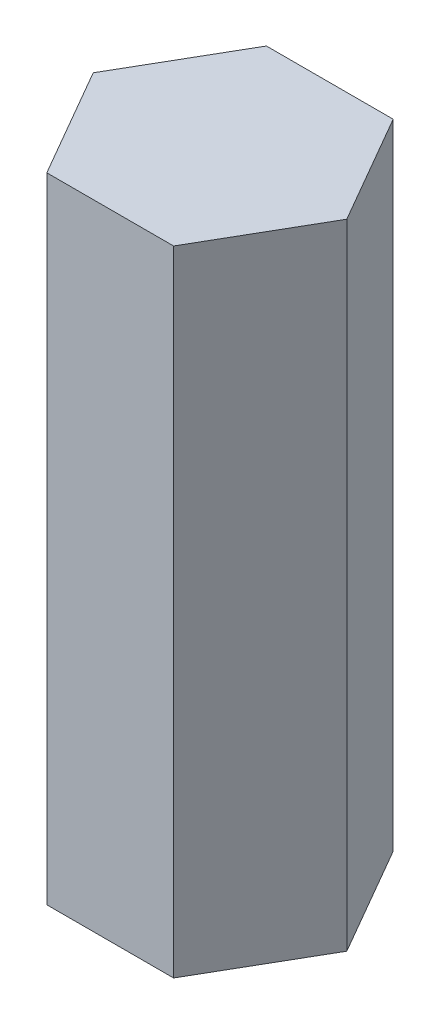
SolidWorks part; units mm, degrees
ref_plane "前视基准面" through (0, 0, 0) normal (0, 0, 1) x (1, 0, 0)
ref_plane "上视基准面" through (0, 0, 0) normal (0, 1, 0) x (1, 0, 0)
ref_plane "右视基准面" through (0, 0, 0) normal (1, 0, 0) x (0, 0, -1)
sketch "草图1" plane through (0, 0, 0) normal (0, 1, 0) x (1, 0, 0)
  line L1 (15, 0) -> (7.5, 12.9904)
  line L2 (7.5, 12.9904) -> (-7.5, 12.9904)
  line L3 (-7.5, 12.9904) -> (-15, 0)
  line L4 (-15, 0) -> (-7.5, -12.9904)
  line L5 (-7.5, -12.9904) -> (7.5, -12.9904)
  line L6 (7.5, -12.9904) -> (15, 0)
  circle A0 centre (0, 0) radius 12.9904 construction
extrude "凸台-拉伸1" add sketch "草图1" along normal blind 75
